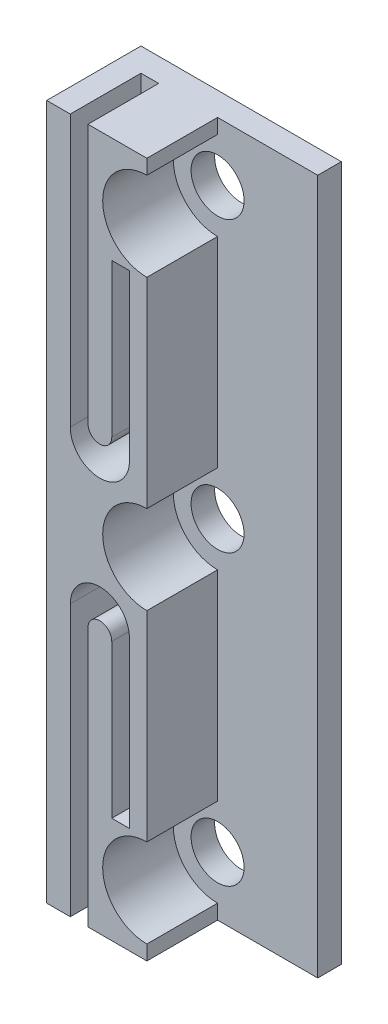
SolidWorks part; units mm, degrees
ref_plane "Plan de face" through (0, 0, 0) normal (0, 0, 1) x (1, 0, 0)
ref_plane "Plan de dessus" through (0, 0, 0) normal (0, 1, 0) x (1, 0, 0)
ref_plane "Plan de droite" through (0, 0, 0) normal (1, 0, 0) x (0, 0, -1)
sketch "Esquisse1" plane through (0, 0, 0) normal (0, 0, 1) x (1, 0, 0)
  line L1 (0, 0) -> (17, 0)
  line L2 (0, 0) -> (0, -59)
  line L3 (0, -59) -> (17, -59)
  line L4 (17, 0) -> (17, -59)
  dimension "D1" = 17
  dimension "D2" = 59
extrude "Boss.-Extru.1" add sketch "Esquisse1" along normal blind 2
sketch "Esquisse2" plane through (0, 0, 2) normal (0, 0, 1) x (1, 0, 0)
  line L0 (0, -59) -> (17, -59) construction
  line L1 (0, 0) -> (8.5, 0)
  line L2 (0, 0) -> (0, -59)
  line L3 (0, -59) -> (8.5, -59)
  line L4 (8.5, 0) -> (8.5, -59)
extrude "Boss.-Extru.2" add sketch "Esquisse2" along normal blind 6
sketch "Esquisse3" plane through (0, 0, 8) normal (0, 0, 1) x (1, 0, 0)
  line L0 (0, -59) -> (8.5, -59) construction
  line L1 (2, -59) -> (3.5, -59)
  line L2 (2, -59) -> (2, 0)
  line L3 (2, 0) -> (3.5, 0)
  line L4 (3.5, -59) -> (3.5, 0)
  line L5 (8.5, 0) -> (0, 0) construction
  line L6 (8.5, -59) -> (8.5, 0) construction
  line L7 (2, -23) -> (3.5, -23)
  line L8 (5.5199, -50) -> (7.0199, -50)
  line L9 (5.5199, -50) -> (5.5199, -9)
  line L10 (5.5199, -9) -> (7.0199, -9)
  line L11 (7.0199, -50) -> (7.0199, -9)
  line L12 (3.5, -37) -> (5.5199, -37)
  line L13 (3.5, -23) -> (5.5199, -23)
  line L14 (5.5199, -23) -> (7.0908, -23)
  line L15 (2, -36) -> (3.5, -36)
  line L16 (3.5, -36) -> (5.5199, -36)
  line L17 (5.5199, -36) -> (7.0199, -36)
  line L18 (3.5, -22) -> (5.5199, -22)
  arc A0 (2, -23) -> (7.0199, -23) centre (4.51, -23) ccw
  arc A1 (3.5, -37) -> (5.5199, -37) centre (4.51, -37) cw
  arc A3 (2, -36) -> (7.0199, -36) centre (4.51, -36) cw
  arc A4 (3.5, -22) -> (5.5199, -22) centre (4.51, -22) ccw
  point P14 (6.2699, -9)
  line M10 (0, -59) -> (8.5, -59)
  line M12 (8.5, 0) -> (0, 0)
  dimension "D1" = 1.5
  dimension "D2" = 5
  dimension "D3" = 1.5
  dimension "D4" = 9
  dimension "D5" = 9
  dimension "D6" = 13
  dimension "D7" = 14
  dimension "D8" = 14
  dimension "D9" = 1
  dimension "D10" = 1
extrude "Enlèv. mat.-Extru.1" cut sketch "Esquisse3" against normal blind 6 contours L9 L14 L11 L10 | L7 A0 L4 | L9 A0 L14 | L17 L9 L8 L11 | L15 L2 L4 M10 | A3 L4 L16 A1 L9 | A3 L15 L4 | A3 L9 L17 | A4 L13 L4 A0 L9 | L2 L7 L4 M12 | A4 L4 L13 | A4 L13 L9 | L4 A1 L16 | L16 A1 L9
sketch "Esquisse4" plane through (0, 0, 8) normal (0, 0, 1) x (1, 0, 0)
  line L2 (3.5, -59) -> (8.5, -59) construction
  line L3 (17, -59) -> (17, 0) construction
  line L4 (0, 0) -> (0, -59) construction
  line L5 (8.5, -59) -> (8.5, 0) construction
  line L6 (8.5, 0) -> (3.5, 0) construction
  circle A0 centre (8.5, -29.5) radius 2.25
  circle A1 centre (8.5, -54) radius 2.25
  circle A2 centre (8.5, -5) radius 2.25
  point P8 (6, -59)
  dimension "D1" = 4.5
  dimension "D2" = 4.5
  dimension "D3" = 4.5
  dimension "D4" = 29.5
  dimension "D5" = 17
  dimension "D6" = 5
  dimension "D7" = 8.5
  dimension "D8" = 5
extrude "Enlèv. mat.-Extru.4" cut sketch "Esquisse4" against normal blind 22
sketch "Esquisse6" plane through (0, 0, 8) normal (0, 0, 1) x (1, 0, 0)
  circle A0 centre (8.5, -29.5) radius 3.75
  circle A1 centre (8.5, -5) radius 3.75
  circle A2 centre (8.5, -54) radius 3.75
  dimension "D1" = 7.5
  dimension "D2" = 7.5
  dimension "D3" = 7.5
extrude "Enlèv. mat.-Extru.5" cut sketch "Esquisse6" against normal blind 6
